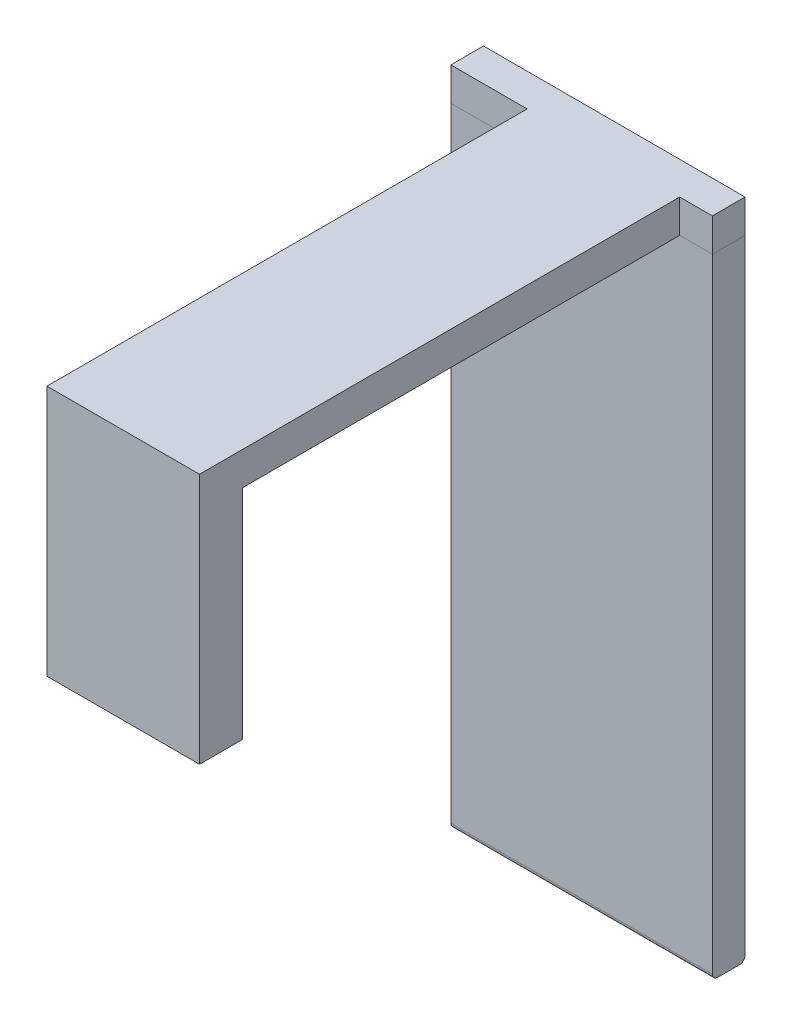
SolidWorks part; units mm, degrees
ref_plane "前视基准面" through (0, 0, 0) normal (0, 0, 1) x (1, 0, 0)
ref_plane "上视基准面" through (0, 0, 0) normal (0, 1, 0) x (1, 0, 0)
ref_plane "右视基准面" through (0, 0, 0) normal (1, 0, 0) x (0, 0, -1)
other "Configuration Table"
sketch "草图1" plane through (0, 0, 0) normal (0, 1, 0) x (1, 0, 0)
  line L1 (0, 0) -> (3.5323, 0)
  line L5 (0, 0) -> (24, 0)
  line L6 (0, 0) -> (0, -3)
  line L7 (0, -3) -> (24, -3)
  line L8 (24, 0) -> (24, -3)
  dimension "D1" = 24
  dimension "D2" = 3
extrude "凸台-拉伸1" add sketch "草图1" along normal blind 57.7 contours L8 L5 L1 L6 L7
sketch "草图2" plane through (0, 0, 3) normal (0, 0, 1) x (1, 0, 0)
  line L0 (0, 57.7) -> (24, 57.7) construction
  line L1 (0, 57.7) -> (24, 57.7)
  line L2 (0, 57.7) -> (0, 60.748)
  line L3 (0, 60.748) -> (24, 60.748)
  line L4 (24, 57.7) -> (24, 60.748)
  line L5 (24, 57.7) -> (24, 0) construction
extrude "凸台-拉伸2" add sketch "草图2" along normal blind 40.1 and the other way up to surface (3 mm away) separate body other way up to face at (12, 28.85, 0)
sketch "草图3" plane through (0, 57.7, 0) normal (0, -1, 0) x (1, 0, 0)
  line L0 (24, 43.1) -> (24, 0) construction
  line L1 (0, 43.1) -> (24, 43.1)
  line L2 (0, 43.1) -> (0, 47.0573)
  line L3 (0, 47.0573) -> (24, 47.0573)
  line L4 (24, 43.1) -> (24, 47.0573)
extrude "凸台-拉伸4" add sketch "草图3" along normal blind 20 and the other way up to surface (3.048 mm away) other way up to face at (12, 60.748, 21.55)
sketch "草图4" plane through (0, 37.7, 0) normal (0, -1, 0) x (1, 0, 0)
  line L0 (0, 3) -> (24, 3) construction
  line L1 (0, 47.0573) -> (7, 47.0573)
  line L2 (0, 47.0573) -> (0, 3)
  line L3 (0, 3) -> (7, 3)
  line L4 (7, 47.0573) -> (7, 3)
  line L5 (24, 0) -> (24, 43.1) construction
  dimension "D1" = 17
extrude "切除-拉伸1" cut sketch "草图4" against normal blind 51
sketch "草图5" plane through (0, 37.7, 0) normal (0, -1, 0) x (1, 0, 0)
  line L0 (0, 3) -> (24, 3) construction
  line L1 (24, 47.0573) -> (21, 47.0573)
  line L2 (24, 47.0573) -> (24, 3)
  line L3 (24, 3) -> (21, 3)
  line L4 (21, 47.0573) -> (21, 3)
  dimension "D1" = 3
extrude "切除-拉伸2" cut sketch "草图5" against normal blind 51
fillet "圆角1" radius 0.5 2 edges at (12, 0, 0) (12, 0, 3)
